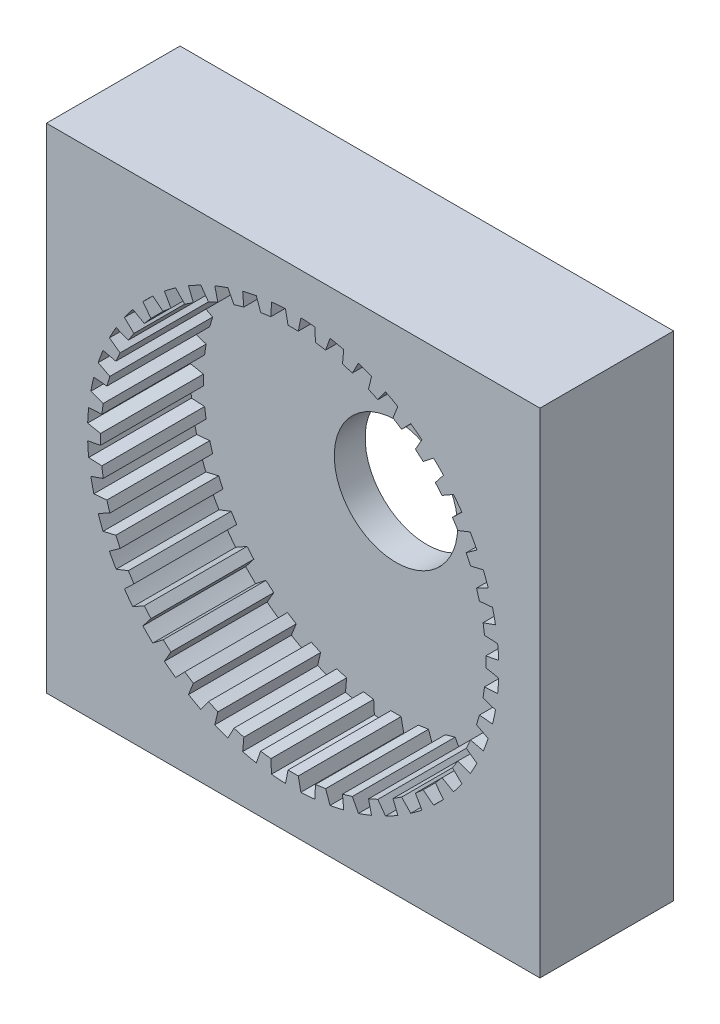
SolidWorks part; units mm, degrees
ref_plane "Front Plane" through (0, 0, 0) normal (0, 0, 1) x (1, 0, 0)
ref_plane "Top Plane" through (0, 0, 0) normal (0, 1, 0) x (1, 0, 0)
ref_plane "Right Plane" through (0, 0, 0) normal (1, 0, 0) x (0, 0, -1)
sketch "Sketch2" plane through (0, 0, 0) normal (0, 0, 1) x (1, 0, 0)
  line L0 (24, 48) -> (24, 0) construction
  line L1 (0, 0) -> (48, 0)
  line L2 (0, 0) -> (0, 48)
  line L3 (0, 48) -> (48, 48)
  line L4 (48, 0) -> (48, 48)
  circle A0 centre (24, 24) radius 6
  dimension "D2" = 12
  dimension "D1" = 48
extrude "Boss-Extrude2" add sketch "Sketch2" along normal blind 3
sketch "Sketch3" plane through (0, 0, 3) normal (0, 0, 1) x (1, 0, 0)
  line L1 (0, 48) -> (48, 48)
  line L2 (0, 48) -> (0, 0)
  line L3 (0, 0) -> (48, 0)
  line L4 (48, 48) -> (48, 0)
  circle A0 centre (24, 24) radius 20
  dimension "D1" = 40
extrude "Boss-Extrude3" add sketch "Sketch3" along normal blind 10
sketch "Sketch4" plane through (0, 0, 13) normal (0, 0, 1) x (1, 0, 0)
  line L0 (24, 24) -> (24, 44) construction
  line L1 (23.5, 42.7318) -> (24.5, 42.7318)
  line L2 (23.25, 44) -> (24.75, 44)
  line L3 (24.75, 44) -> (24.5, 42.7318)
  line L4 (23.25, 44) -> (23.5, 42.7318)
  line L5 (26.1039, 43.9032) -> (26.1709, 42.6123)
  line L6 (26.1709, 42.6123) -> (27.1607, 42.47)
  line L7 (27.5887, 43.6897) -> (27.1607, 42.47)
  line L8 (26.1039, 43.9032) -> (27.5887, 43.6897)
  line L9 (28.915, 43.4012) -> (28.7976, 42.1139)
  line L10 (28.7976, 42.1139) -> (29.7571, 41.8322)
  line L11 (30.3543, 42.9786) -> (29.7571, 41.8322)
  line L12 (28.915, 43.4012) -> (30.3543, 42.9786)
  line L13 (31.6261, 42.5042) -> (31.3267, 41.2468)
  line L14 (31.3267, 41.2468) -> (32.2363, 40.8314)
  line L15 (32.9905, 41.8811) -> (32.2363, 40.8314)
  line L16 (31.6261, 42.5042) -> (32.9905, 41.8811)
  line L17 (34.1819, 41.2306) -> (33.7066, 40.0285)
  line L18 (33.7066, 40.0285) -> (34.5478, 39.4879)
  line L19 (35.4438, 40.4196) -> (34.5478, 39.4879)
  line L20 (34.1819, 41.2306) -> (35.4438, 40.4196)
  line L21 (36.5304, 39.6061) -> (35.8889, 38.484)
  line L22 (35.8889, 38.484) -> (36.6446, 37.8291)
  line L23 (37.664, 38.6238) -> (36.6446, 37.8291)
  line L24 (36.5304, 39.6061) -> (37.664, 38.6238)
  line L25 (38.6238, 37.664) -> (37.8291, 36.6446)
  line L26 (37.8291, 36.6446) -> (38.484, 35.8889)
  line L27 (39.6061, 36.5304) -> (38.484, 35.8889)
  line L28 (38.6238, 37.664) -> (39.6061, 36.5304)
  line L29 (40.4196, 35.4438) -> (39.4879, 34.5478)
  line L30 (39.4879, 34.5478) -> (40.0285, 33.7066)
  line L31 (41.2306, 34.1819) -> (40.0285, 33.7066)
  line L32 (40.4196, 35.4438) -> (41.2306, 34.1819)
  line L33 (41.8811, 32.9905) -> (40.8314, 32.2363)
  line L34 (40.8314, 32.2363) -> (41.2468, 31.3267)
  line L35 (42.5042, 31.6261) -> (41.2468, 31.3267)
  line L36 (41.8811, 32.9905) -> (42.5042, 31.6261)
  line L37 (42.9786, 30.3543) -> (41.8322, 29.7571)
  line L38 (41.8322, 29.7571) -> (42.1139, 28.7976)
  line L39 (43.4012, 28.915) -> (42.1139, 28.7976)
  line L40 (42.9786, 30.3543) -> (43.4012, 28.915)
  line L41 (43.6897, 27.5887) -> (42.47, 27.1607)
  line L42 (42.47, 27.1607) -> (42.6123, 26.1709)
  line L43 (43.9032, 26.1039) -> (42.6123, 26.1709)
  line L44 (43.6897, 27.5887) -> (43.9032, 26.1039)
  line L45 (44, 24.75) -> (42.7318, 24.5)
  line L46 (42.7318, 24.5) -> (42.7318, 23.5)
  line L47 (44, 23.25) -> (42.7318, 23.5)
  line L48 (44, 24.75) -> (44, 23.25)
  line L49 (43.9032, 21.8961) -> (42.6123, 21.8291)
  line L50 (42.6123, 21.8291) -> (42.47, 20.8393)
  line L51 (43.6897, 20.4113) -> (42.47, 20.8393)
  line L52 (43.9032, 21.8961) -> (43.6897, 20.4113)
  line L53 (43.4012, 19.085) -> (42.1139, 19.2024)
  line L54 (42.1139, 19.2024) -> (41.8322, 18.2429)
  line L55 (42.9786, 17.6457) -> (41.8322, 18.2429)
  line L56 (43.4012, 19.085) -> (42.9786, 17.6457)
  line L57 (42.5042, 16.3739) -> (41.2468, 16.6733)
  line L58 (41.2468, 16.6733) -> (40.8314, 15.7637)
  line L59 (41.8811, 15.0095) -> (40.8314, 15.7637)
  line L60 (42.5042, 16.3739) -> (41.8811, 15.0095)
  line L61 (41.2306, 13.8181) -> (40.0285, 14.2934)
  line L62 (40.0285, 14.2934) -> (39.4879, 13.4522)
  line L63 (40.4196, 12.5562) -> (39.4879, 13.4522)
  line L64 (41.2306, 13.8181) -> (40.4196, 12.5562)
  line L65 (39.6061, 11.4696) -> (38.484, 12.1111)
  line L66 (38.484, 12.1111) -> (37.8291, 11.3554)
  line L67 (38.6238, 10.336) -> (37.8291, 11.3554)
  line L68 (39.6061, 11.4696) -> (38.6238, 10.336)
  line L69 (37.664, 9.3762) -> (36.6446, 10.1709)
  line L70 (36.6446, 10.1709) -> (35.8889, 9.516)
  line L71 (36.5304, 8.3939) -> (35.8889, 9.516)
  line L72 (37.664, 9.3762) -> (36.5304, 8.3939)
  line L73 (35.4438, 7.5804) -> (34.5478, 8.5121)
  line L74 (34.5478, 8.5121) -> (33.7066, 7.9715)
  line L75 (34.1819, 6.7694) -> (33.7066, 7.9715)
  line L76 (35.4438, 7.5804) -> (34.1819, 6.7694)
  line L77 (32.9905, 6.1189) -> (32.2363, 7.1686)
  line L78 (32.2363, 7.1686) -> (31.3267, 6.7532)
  line L79 (31.6261, 5.4958) -> (31.3267, 6.7532)
  line L80 (32.9905, 6.1189) -> (31.6261, 5.4958)
  line L81 (30.3543, 5.0214) -> (29.7571, 6.1678)
  line L82 (29.7571, 6.1678) -> (28.7976, 5.8861)
  line L83 (28.915, 4.5988) -> (28.7976, 5.8861)
  line L84 (30.3543, 5.0214) -> (28.915, 4.5988)
  line L85 (27.5887, 4.3103) -> (27.1607, 5.53)
  line L86 (27.1607, 5.53) -> (26.1709, 5.3877)
  line L87 (26.1039, 4.0968) -> (26.1709, 5.3877)
  line L88 (27.5887, 4.3103) -> (26.1039, 4.0968)
  line L89 (24.75, 4) -> (24.5, 5.2682)
  line L90 (24.5, 5.2682) -> (23.5, 5.2682)
  line L91 (23.25, 4) -> (23.5, 5.2682)
  line L92 (24.75, 4) -> (23.25, 4)
  line L93 (21.8961, 4.0968) -> (21.8291, 5.3877)
  line L94 (21.8291, 5.3877) -> (20.8393, 5.53)
  line L95 (20.4113, 4.3103) -> (20.8393, 5.53)
  line L96 (21.8961, 4.0968) -> (20.4113, 4.3103)
  line L97 (19.085, 4.5988) -> (19.2024, 5.8861)
  line L98 (19.2024, 5.8861) -> (18.2429, 6.1678)
  line L99 (17.6457, 5.0214) -> (18.2429, 6.1678)
  line L100 (19.085, 4.5988) -> (17.6457, 5.0214)
  line L101 (16.3739, 5.4958) -> (16.6733, 6.7532)
  line L102 (16.6733, 6.7532) -> (15.7637, 7.1686)
  line L103 (15.0095, 6.1189) -> (15.7637, 7.1686)
  line L104 (16.3739, 5.4958) -> (15.0095, 6.1189)
  line L105 (13.8181, 6.7694) -> (14.2934, 7.9715)
  line L106 (14.2934, 7.9715) -> (13.4522, 8.5121)
  line L107 (12.5562, 7.5804) -> (13.4522, 8.5121)
  line L108 (13.8181, 6.7694) -> (12.5562, 7.5804)
  line L109 (11.4696, 8.3939) -> (12.1111, 9.516)
  line L110 (12.1111, 9.516) -> (11.3554, 10.1709)
  line L111 (10.336, 9.3762) -> (11.3554, 10.1709)
  line L112 (11.4696, 8.3939) -> (10.336, 9.3762)
  line L113 (9.3762, 10.336) -> (10.1709, 11.3554)
  line L114 (10.1709, 11.3554) -> (9.516, 12.1111)
  line L115 (8.3939, 11.4696) -> (9.516, 12.1111)
  line L116 (9.3762, 10.336) -> (8.3939, 11.4696)
  line L117 (7.5804, 12.5562) -> (8.5121, 13.4522)
  line L118 (8.5121, 13.4522) -> (7.9715, 14.2934)
  line L119 (6.7694, 13.8181) -> (7.9715, 14.2934)
  line L120 (7.5804, 12.5562) -> (6.7694, 13.8181)
  line L121 (6.1189, 15.0095) -> (7.1686, 15.7637)
  line L122 (7.1686, 15.7637) -> (6.7532, 16.6733)
  line L123 (5.4958, 16.3739) -> (6.7532, 16.6733)
  line L124 (6.1189, 15.0095) -> (5.4958, 16.3739)
  line L125 (5.0214, 17.6457) -> (6.1678, 18.2429)
  line L126 (6.1678, 18.2429) -> (5.8861, 19.2024)
  line L127 (4.5988, 19.085) -> (5.8861, 19.2024)
  line L128 (5.0214, 17.6457) -> (4.5988, 19.085)
  line L129 (4.3103, 20.4113) -> (5.53, 20.8393)
  line L130 (5.53, 20.8393) -> (5.3877, 21.8291)
  line L131 (4.0968, 21.8961) -> (5.3877, 21.8291)
  line L132 (4.3103, 20.4113) -> (4.0968, 21.8961)
  line L133 (4, 23.25) -> (5.2682, 23.5)
  line L134 (5.2682, 23.5) -> (5.2682, 24.5)
  line L135 (4, 24.75) -> (5.2682, 24.5)
  line L136 (4, 23.25) -> (4, 24.75)
  line L137 (4.0968, 26.1039) -> (5.3877, 26.1709)
  line L138 (5.3877, 26.1709) -> (5.53, 27.1607)
  line L139 (4.3103, 27.5887) -> (5.53, 27.1607)
  line L140 (4.0968, 26.1039) -> (4.3103, 27.5887)
  line L141 (4.5988, 28.915) -> (5.8861, 28.7976)
  line L142 (5.8861, 28.7976) -> (6.1678, 29.7571)
  line L143 (5.0214, 30.3543) -> (6.1678, 29.7571)
  line L144 (4.5988, 28.915) -> (5.0214, 30.3543)
  line L145 (5.4958, 31.6261) -> (6.7532, 31.3267)
  line L146 (6.7532, 31.3267) -> (7.1686, 32.2363)
  line L147 (6.1189, 32.9905) -> (7.1686, 32.2363)
  line L148 (5.4958, 31.6261) -> (6.1189, 32.9905)
  line L149 (6.7694, 34.1819) -> (7.9715, 33.7066)
  line L150 (7.9715, 33.7066) -> (8.5121, 34.5478)
  line L151 (7.5804, 35.4438) -> (8.5121, 34.5478)
  line L152 (6.7694, 34.1819) -> (7.5804, 35.4438)
  line L153 (8.3939, 36.5304) -> (9.516, 35.8889)
  line L154 (9.516, 35.8889) -> (10.1709, 36.6446)
  line L155 (9.3762, 37.664) -> (10.1709, 36.6446)
  line L156 (8.3939, 36.5304) -> (9.3762, 37.664)
  line L157 (10.336, 38.6238) -> (11.3554, 37.8291)
  line L158 (11.3554, 37.8291) -> (12.1111, 38.484)
  line L159 (11.4696, 39.6061) -> (12.1111, 38.484)
  line L160 (10.336, 38.6238) -> (11.4696, 39.6061)
  line L161 (12.5562, 40.4196) -> (13.4522, 39.4879)
  line L162 (13.4522, 39.4879) -> (14.2934, 40.0285)
  line L163 (13.8181, 41.2306) -> (14.2934, 40.0285)
  line L164 (12.5562, 40.4196) -> (13.8181, 41.2306)
  line L165 (15.0095, 41.8811) -> (15.7637, 40.8314)
  line L166 (15.7637, 40.8314) -> (16.6733, 41.2468)
  line L167 (16.3739, 42.5042) -> (16.6733, 41.2468)
  line L168 (15.0095, 41.8811) -> (16.3739, 42.5042)
  line L169 (17.6457, 42.9786) -> (18.2429, 41.8322)
  line L170 (18.2429, 41.8322) -> (19.2024, 42.1139)
  line L171 (19.085, 43.4012) -> (19.2024, 42.1139)
  line L172 (17.6457, 42.9786) -> (19.085, 43.4012)
  line L173 (20.4113, 43.6897) -> (20.8393, 42.47)
  line L174 (20.8393, 42.47) -> (21.8291, 42.6123)
  line L175 (21.8961, 43.9032) -> (21.8291, 42.6123)
  line L176 (20.4113, 43.6897) -> (21.8961, 43.9032)
  line L177 (24, 24) -> (24.5, 42.7318) construction
  line L178 (24, 24) -> (27.1607, 42.47) construction
  circle A0 centre (24, 24) radius 20 construction
  circle A1 centre (24, 24) radius 20 construction
  point P7 (24, 42.7318)
  point P10 (9.5417, 38.416)
  point P11 (23.8754, 24)
  dimension "D1" = 1
  dimension "D2" = 1.5
  dimension "D3" = 1.2682
  dimension "D4" = 8.182
extrude "Boss-Extrude6" add sketch "Sketch4" against normal up to surface (10 mm away) up to face at (30, 24, 3)
equation "\"motor_diameter\"= 38mm"
equation "\"motor_length\"= 60mm"
equation "\"shaft_diameter\"= 5mm"
equation "\"shaft_length\"= 10mm"
equation "\"D1@Sketch2\"=\"motor_diameter\" + 10mm"
equation "\"planet_gear_diameter\"= 10mm"
equation "\"D2@Sketch2\"=\"planet_gear_diameter\" + 2mm"
equation "\"solar_diameter\"= 40mm"
equation "\"D1@Sketch3\"=\"solar_diameter\""
equation "\"solar_thickness\"= 10mm"
equation "\"D1@Boss-Extrude3\"=\"solar_thickness\""
